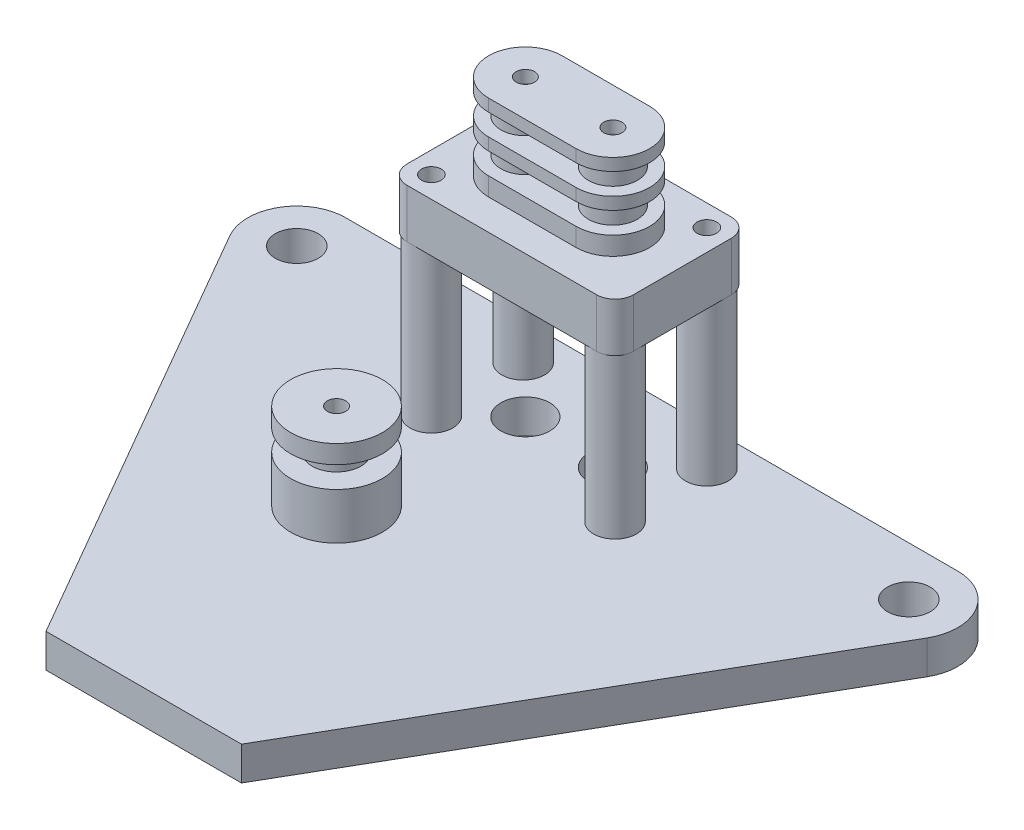
SolidWorks part; units mm, degrees
ref_plane "正面" through (0, 0, 0) normal (0, 0, 1) x (1, 0, 0)
ref_plane "平面" through (0, 0, 0) normal (0, 1, 0) x (1, 0, 0)
ref_plane "右側面" through (0, 0, 0) normal (1, 0, 0) x (0, 0, -1)
sketch "ｽｹｯﾁ1" plane through (0, 0, 0) normal (0, 1, 0) x (1, 0, 0)
  line L0 (0, -41.5) -> (0, 41.5) construction
  line L2 (-56.9295, 29.5022) -> (-15.9664, -41.5)
  line L3 (-15.9664, -41.5) -> (15.9664, -41.5)
  line L4 (56.9295, 29.5022) -> (15.9664, -41.5)
  line L7 (-50, 41.5) -> (50, 41.5)
  line L8 (0, 28) -> (-7.15, 28) construction
  line L9 (-3.15, 28) -> (-3.15, 41.5) construction
  line L10 (3.15, 28) -> (3.15, 41.5) construction
  line L11 (-50, 33.5) -> (0, 33.5) construction
  line L12 (-7.15, 32) -> (7.15, 32) construction
  line L13 (-10, 4) -> (0, 4) construction
  line L14 (-10, 5.5) -> (0, 5.5) construction
  circle A0 centre (-50, 33.5) radius 3.5
  arc A1 (-50, 41.5) -> (-56.9295, 29.5022) centre (-50, 33.5) ccw
  arc A2 (-56.9295, 29.5022) -> (-50, 41.5) centre (-50, 33.5) ccw construction
  arc A3 (56.9295, 29.5022) -> (50, 41.5) centre (50, 33.5) cw construction
  arc A4 (50, 41.5) -> (56.9295, 29.5022) centre (50, 33.5) cw
  circle A5 centre (50, 33.5) radius 3.5
  circle A6 centre (-7.15, 28) radius 4
  circle A7 centre (-7.15, 28) radius 1.5 construction
  circle A8 centre (7.15, 28) radius 4
  circle A9 centre (7.15, 28) radius 1.5 construction
  circle A10 centre (-10, 0) radius 1.5
  circle A11 centre (-10, 0) radius 4 construction
  point P15 (0, 0)
  dimension "D1" = 7
  dimension "D2" = 16
  dimension "D5" = 3
  dimension "D6" = 8
  dimension "D3" = 100
  dimension "D4" = 75
  dimension "D7" = 6.3
  dimension "D8" = 1.5
  dimension "D10" = 1.5
  dimension "D11" = 28
  dimension "10" = 10
extrude "ﾎﾞｽ - 押し出し1" add sketch "ｽｹｯﾁ1" along normal blind 5.5
sketch "ｽｹｯﾁ3" plane through (0, 5.5, 0) normal (0, 1, 0) x (1, 0, 0)
  circle A0 centre (-10, 0) radius 7.5
  circle A1 centre (-10, 0) radius 1.5 construction
  circle A2 centre (-10, 0) radius 1.5
  dimension "D1" = 15
extrude "ﾎﾞｽ - 押し出し2" add sketch "ｽｹｯﾁ3" along normal blind 7.6 separate body
sketch "ｽｹｯﾁ4" plane through (0, 13.1, 0) normal (0, 1, 0) x (1, 0, 0)
  circle A0 centre (-10, 0) radius 3
  circle A1 centre (-10, 0) radius 1.5 construction
  circle A2 centre (-10, 0) radius 1.5
  dimension "D1" = 6
extrude "ﾎﾞｽ - 押し出し3" add sketch "ｽｹｯﾁ4" along normal blind 3.5 separate body
sketch "ｽｹｯﾁ5" plane through (0, 13.1, 0) normal (0, 1, 0) x (1, 0, 0)
  circle A0 centre (-10, 0) radius 3.1
  circle A1 centre (-10, 0) radius 4
  dimension "D1" = 6.2
  dimension "D2" = 8
extrude "ﾎﾞｽ - 押し出し4" add sketch "ｽｹｯﾁ5" along normal blind 3 separate body
sketch "ｽｹｯﾁ6" plane through (0, 16.6, 0) normal (0, 1, 0) x (1, 0, 0)
  circle A0 centre (-10, 0) radius 1.5 construction
  circle A1 centre (-10, 0) radius 1.5
  circle A2 centre (-10, 0) radius 7.5
  dimension "D1" = 15
extrude "ﾎﾞｽ - 押し出し5" add sketch "ｽｹｯﾁ6" along normal blind 3 separate body
sketch "ｽｹｯﾁ7" plane through (0, 5.5, 0) normal (0, 1, 0) x (1, 0, 0)
  line L5 (15, 20.5) -> (-15, 20.5) construction
  line L6 (15, 20.5) -> (15, 35.5) construction
  line L7 (15, 35.5) -> (-15, 35.5) construction
  line L8 (-15, 20.5) -> (-15, 35.5) construction
  line L9 (15, 20.5) -> (-15, 35.5) construction
  line L10 (15, 35.5) -> (-15, 20.5) construction
  circle A8 centre (-15, 35.5) radius 1.6
  circle A9 centre (-15, 20.5) radius 1.6
  circle A10 centre (15, 20.5) radius 1.6
  circle A11 centre (15, 35.5) radius 1.6
  circle A12 centre (-15, 35.5) radius 3.5
  circle A13 centre (-15, 20.5) radius 3.5
  circle A14 centre (15, 35.5) radius 3.5
  circle A15 centre (15, 20.5) radius 3.5
  point P0 (0, 28)
  dimension "D1" = 30
  dimension "D2" = 15
  dimension "D3" = 3.2
  dimension "D4" = 7
extrude "ﾎﾞｽ - 押し出し6" add sketch "ｽｹｯﾁ7" along normal blind 26.1 separate body
sketch "ｽｹｯﾁ8" plane through (0, 5.5, 0) normal (0, 1, 0) x (1, 0, 0)
  circle A0 centre (15, 35.5) radius 1.6 construction
  circle A1 centre (15, 20.5) radius 1.6 construction
  circle A3 centre (-15, 20.5) radius 1.6 construction
  circle A4 centre (-15, 35.5) radius 1.6 construction
  circle A5 centre (15, 35.5) radius 1.6
  circle A6 centre (-15, 20.5) radius 1.6
  circle A7 centre (-15, 35.5) radius 1.6
  circle A8 centre (15, 20.5) radius 1.6
extrude "ｶｯﾄ - 押し出し1" cut sketch "ｽｹｯﾁ8" against normal through all
sketch "ｽｹｯﾁ9" plane through (0, 31.6, 0) normal (0, 1, 0) x (1, 0, 0)
  line L1 (15.5, 17) -> (-15.5, 17)
  line L2 (18.5, 20) -> (18.5, 36)
  line L3 (15.5, 39) -> (-15.5, 39)
  line L4 (-18.5, 20) -> (-18.5, 36)
  line L5 (18.5, 17) -> (-18.5, 39) construction
  line L6 (18.5, 39) -> (-18.5, 17) construction
  circle A0 centre (-15, 35.5) radius 1.6 construction
  circle A1 centre (-15, 20.5) radius 1.6 construction
  circle A2 centre (15, 35.5) radius 1.6 construction
  circle A3 centre (15, 35.5) radius 1.6
  circle A4 centre (-15, 20.5) radius 1.6
  circle A5 centre (-15, 35.5) radius 1.6
  circle A6 centre (-15, 35.5) radius 3.5 construction
  arc A7 (18.5, 36) -> (15.5, 39) centre (15.5, 36) ccw
  arc A8 (15.5, 17) -> (18.5, 20) centre (15.5, 20) ccw
  arc A9 (-15.5, 17) -> (-18.5, 20) centre (-15.5, 20) cw
  arc A10 (-15.5, 39) -> (-18.5, 36) centre (-15.5, 36) ccw
  circle A11 centre (7.15, 28) radius 1.5 construction
  circle A12 centre (-7.15, 28) radius 1.5 construction
  circle A13 centre (7.15, 28) radius 1.5
  circle A14 centre (-7.15, 28) radius 1.5
  point P0 (0, 28)
  dimension "D1" = 3
extrude "ﾎﾞｽ - 押し出し7" add sketch "ｽｹｯﾁ9" along normal blind 8
sketch "ｽｹｯﾁ10" plane through (0, 39.6, 0) normal (0, 1, 0) x (1, 0, 0)
  line L0 (-7.15, 28) -> (7.15, 28) construction
  line L1 (-7.15, 34) -> (7.15, 34)
  line L2 (-7.15, 22) -> (7.15, 22)
  arc A0 (-7.15, 34) -> (-7.15, 22) centre (-7.15, 28) ccw
  arc A1 (7.15, 22) -> (7.15, 34) centre (7.15, 28) ccw
  circle A2 centre (7.15, 28) radius 1.5 construction
  circle A3 centre (-7.15, 28) radius 1.5 construction
  circle A4 centre (7.15, 28) radius 1.5
  circle A5 centre (-7.15, 28) radius 1.5
  point P4 (0, 28)
  dimension "D1" = 6
extrude "ﾎﾞｽ - 押し出し9" add sketch "ｽｹｯﾁ10" along normal blind 3 separate body
sketch "ｽｹｯﾁ11" plane through (0, 42.6, 0) normal (0, 1, 0) x (1, 0, 0)
  circle A0 centre (7.15, 28) radius 1.5 construction
  circle A1 centre (-7.15, 28) radius 1.5 construction
  circle A2 centre (7.15, 28) radius 1.5
  circle A3 centre (-7.15, 28) radius 1.5
  circle A4 centre (-7.15, 28) radius 2.5
  circle A5 centre (7.15, 28) radius 2.5
  dimension "D1" = 5
extrude "ﾎﾞｽ - 押し出し10" add sketch "ｽｹｯﾁ11" along normal blind 3.5 separate body
sketch "ｽｹｯﾁ12" plane through (0, 42.6, 0) normal (0, 1, 0) x (1, 0, 0)
  circle A0 centre (-7.15, 28) radius 2.6
  circle A1 centre (-7.15, 28) radius 4 construction
  circle A2 centre (-7.15, 28) radius 4
  circle A3 centre (7.15, 28) radius 2.6
  circle A4 centre (7.15, 28) radius 4 construction
  circle A5 centre (7.15, 28) radius 4
  dimension "D1" = 5.2
extrude "ﾎﾞｽ - 押し出し11" add sketch "ｽｹｯﾁ12" along normal blind 3 separate body
sketch "ｽｹｯﾁ13" plane through (0, 46.1, 0) normal (0, 1, 0) x (1, 0, 0)
  line L2 (-7.15, 22) -> (7.15, 22)
  line L3 (7.15, 34) -> (-7.15, 34)
  line L4 (-7.15, 22) -> (7.15, 22)
  line L5 (7.15, 34) -> (-7.15, 34)
  circle A0 centre (7.15, 28) radius 1.5 construction
  circle A1 centre (-7.15, 28) radius 1.5 construction
  arc A2 (-7.15, 34) -> (-7.15, 22) centre (-7.15, 28) ccw
  arc A3 (7.15, 22) -> (7.15, 34) centre (7.15, 28) ccw
  arc A4 (-7.15, 34) -> (-7.15, 22) centre (-7.15, 28) ccw
  arc A5 (7.15, 22) -> (7.15, 34) centre (7.15, 28) ccw
  circle A6 centre (7.15, 28) radius 1.5
  circle A7 centre (-7.15, 28) radius 1.5
  dimension "D1" = 0
extrude "ﾎﾞｽ - 押し出し12" add sketch "ｽｹｯﾁ13" along normal blind 2 separate body
pattern_linear "直線ﾊﾟﾀｰﾝ1" count 2 spacing 5.5 along (0, 1, 0) of bodies 118 117 116 114 115
